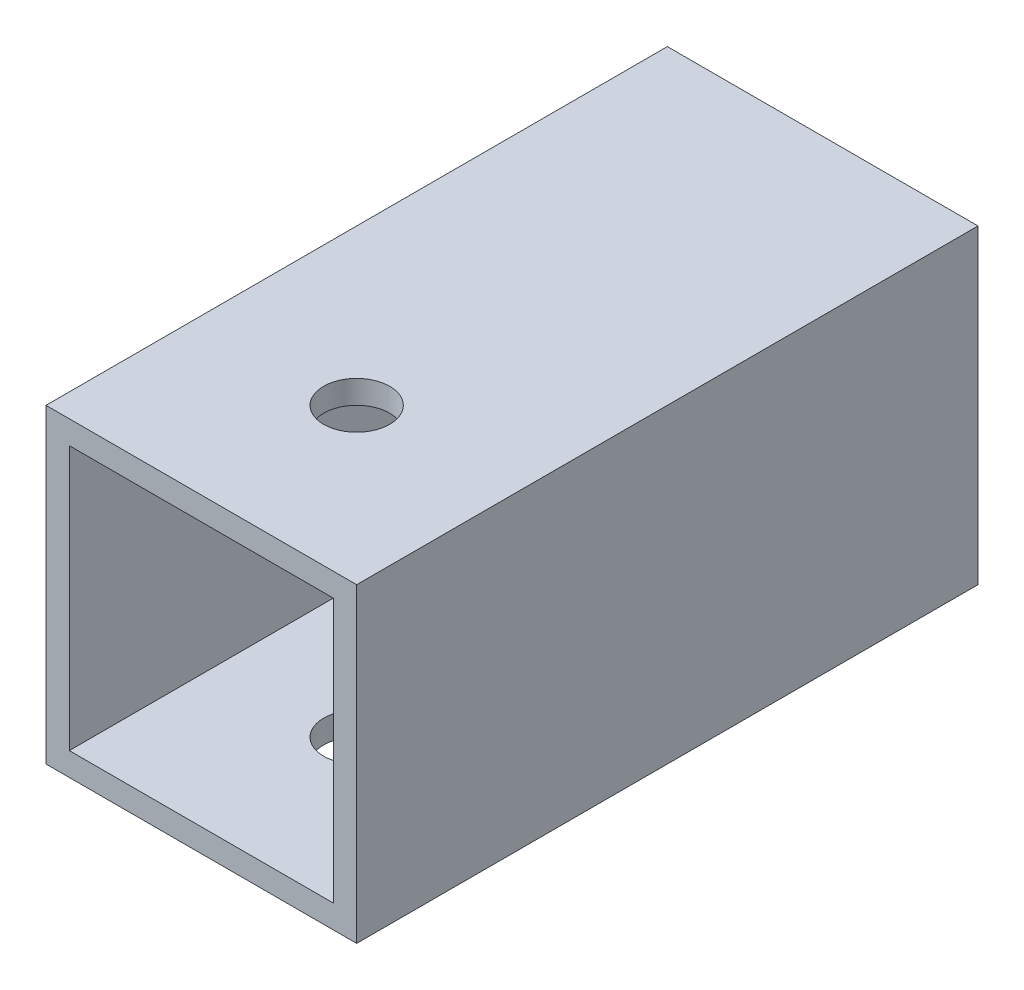
SolidWorks part; units mm, degrees
ref_plane "Front Plane" through (0, 0, 0) normal (0, 0, 1) x (1, 0, 0)
ref_plane "Top Plane" through (0, 0, 0) normal (0, 1, 0) x (1, 0, 0)
ref_plane "Right Plane" through (0, 0, 0) normal (1, 0, 0) x (0, 0, -1)
sketch "Sketch1" plane through (0, 0, 0) normal (0, 0, 1) x (1, 0, 0)
  line L0 (-8.5, -8.5) -> (8.5, -8.5)
  line L1 (-10, -10) -> (10, -10)
  line L2 (-10, -10) -> (-10, 10)
  line L3 (-10, 10) -> (10, 10)
  line L4 (10, -10) -> (10, 10)
  line L5 (-10, -10) -> (10, 10) construction
  line L6 (-10, 10) -> (10, -10) construction
  line L7 (8.5, -8.5) -> (8.5, 8.5)
  line L8 (-8.5, 8.5) -> (8.5, 8.5)
  line L9 (-8.5, -8.5) -> (-8.5, 8.5)
  point P0 (0, 0)
  dimension "D1" = 20
  dimension "D3" = 20
  dimension "D2" = 1.5
extrude "Boss-Extrude1" add sketch "Sketch1" against normal blind 40
sketch "Sketch2" plane through (0, 10, 0) normal (0, 1, 0) x (1, 0, 0)
  line L0 (10, 0) -> (-10, 0) construction
  circle A0 centre (0, 10) radius 2.125
  circle A6 centre (0, 80) radius 2.125
  circle A7 centre (0, 150) radius 2.125
  dimension "D1" = 4.25
  dimension "D2" = 10
extrude "Cut-Extrude1" cut sketch "Sketch2" against normal through all
